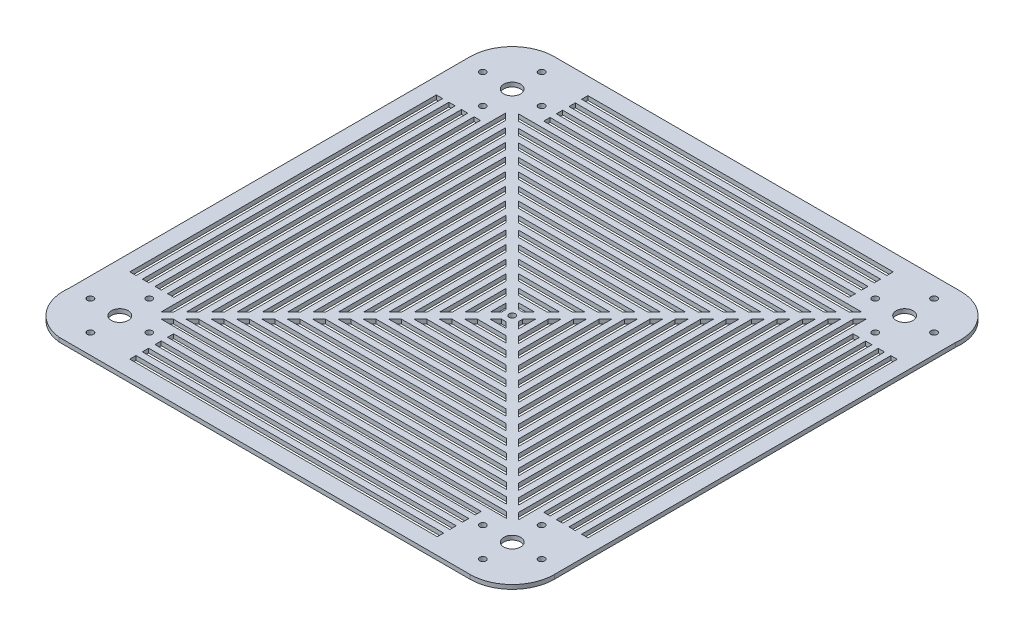
SolidWorks part; units mm, degrees
ref_plane "前视基准面" through (0, 0, 0) normal (0, 0, 1) x (1, 0, 0)
ref_plane "上视基准面" through (0, 0, 0) normal (0, 1, 0) x (1, 0, 0)
ref_plane "右视基准面" through (0, 0, 0) normal (1, 0, 0) x (0, 0, -1)
sketch "草图5" plane through (0, 0, 0) normal (0, 1, 0) x (1, 0, 0)
  line L0 (1.5, 6) -> (5.6645, 10.1645)
  line L5 (-145, 175.0001) -> (144.9999, 175.0001)
  line L6 (-175.0001, 145) -> (-175.0001, -141.539)
  line L7 (-148.4608, -175.0001) -> (145, -175.0001)
  line L8 (174.7909, 141.4627) -> (175.0001, -144.9781)
  line L9 (-175.0001, 175.0001) -> (175.0001, -175.0001) construction
  line L10 (-175, -175) -> (175, 175) construction
  line L13 (0, 0) -> (0, -50000) construction
  line L14 (0, 0) -> (50000, 0) construction
  line L15 (-1.5, 6) -> (1.5, 6)
  line L16 (-6, 1.5) -> (-6, -1.5)
  line L17 (-1.5, -6) -> (1.5, -6)
  line L18 (6, 1.5) -> (6, -1.5)
  line L19 (-6, 6) -> (6, -6) construction
  line L20 (-6, -6) -> (6, 6) construction
  line L21 (-5.6645, 10.1645) -> (5.6645, 10.1645)
  line L22 (-9.9532, 5.4462) -> (-9.9532, -5.4532)
  line L23 (-5.5915, -10.0915) -> (5.606, -10.0915)
  line L24 (10.5146, 6.0146) -> (10.5146, -6.0145)
  line L25 (-10.5, 10.5) -> (10.5, -10.5) construction
  line L26 (-10.5, -10.5) -> (10.5, 10.5) construction
  line L27 (-10.1536, 14.6536) -> (10.1536, 14.6536)
  line L28 (-14.4739, 9.959) -> (-14.4739, -9.9739)
  line L29 (-10.1115, -14.6115) -> (10.142, -14.6115)
  line L30 (15.0552, 10.5552) -> (15.0552, -10.5552)
  line L31 (-15, 15) -> (15, -15) construction
  line L32 (-15, -15) -> (15, 15) construction
  line L33 (-14.6429, 19.1429) -> (14.6428, 19.1429)
  line L34 (-18.9947, 14.4718) -> (-18.9947, -14.4947)
  line L35 (-14.6315, -19.1315) -> (14.678, -19.1315)
  line L36 (19.591, 15.091) -> (19.591, -15.0909)
  line L37 (-19.5, 19.5) -> (19.5, -19.5) construction
  line L38 (-19.5, -19.5) -> (19.5, 19.5) construction
  line L39 (-19.1322, 23.6322) -> (19.1321, 23.6322)
  line L40 (-23.5154, 18.9846) -> (-23.5154, -19.0154)
  line L41 (-19.1515, -23.6515) -> (19.214, -23.6515)
  line L42 (24.1268, 19.6268) -> (24.1268, -19.6267)
  line L43 (-24, 24) -> (24, -24) construction
  line L44 (-24, -24) -> (24, 24) construction
  line L45 (23.6214, 28.1215) -> (-23.6215, 28.1215)
  line L46 (28.6626, 24.1626) -> (28.6626, -24.1625)
  line L47 (23.75, -28.1715) -> (-23.6715, -28.1715)
  line L48 (-28.0362, 23.4973) -> (-28.0362, -23.5362)
  line L49 (28.5, 28.5) -> (-28.5, -28.5) construction
  line L50 (28.5, -28.5) -> (-28.5, 28.5) construction
  line L51 (-28.1108, 32.6108) -> (28.1106, 32.6108)
  line L52 (-32.5569, 28.0101) -> (-32.5569, -28.0569)
  line L53 (-28.1915, -32.6915) -> (28.286, -32.6915)
  line L54 (33.1984, 28.6984) -> (33.1984, -28.6983)
  line L55 (-33, 33) -> (33, -33) construction
  line L56 (-33, -33) -> (33, 33) construction
  line L57 (-32.6001, 37.1001) -> (32.5999, 37.1001)
  line L58 (-37.0777, 32.5229) -> (-37.0777, -32.5777)
  line L59 (-32.7115, -37.2115) -> (32.822, -37.2115)
  line L60 (37.7342, 33.2342) -> (37.7342, -33.2341)
  line L61 (-37.5, 37.5) -> (37.5, -37.5) construction
  line L62 (-37.5, -37.5) -> (37.5, 37.5) construction
  line L63 (-37.0894, 41.5894) -> (37.0891, 41.5894)
  line L64 (-41.5984, 37.0357) -> (-41.5984, -37.0984)
  line L65 (-37.2314, -41.7314) -> (37.358, -41.7314)
  line L66 (42.27, 37.77) -> (42.27, -37.7699)
  line L67 (-42, 42) -> (42, -42) construction
  line L68 (-42, -42) -> (42, 42) construction
  line L69 (-41.5787, 46.0787) -> (41.5784, 46.0787)
  line L70 (-46.1192, 41.5485) -> (-46.1192, -41.6192)
  line L71 (-41.7514, -46.2514) -> (41.894, -46.2514)
  line L72 (46.8058, 42.3058) -> (46.8058, -42.3057)
  line L73 (-46.5, 46.5) -> (46.5, -46.5) construction
  line L74 (-46.5, -46.5) -> (46.5, 46.5) construction
  line L75 (-46.068, 50.568) -> (46.0677, 50.568)
  line L76 (-50.6399, 46.0613) -> (-50.6399, -46.1399)
  line L77 (-46.2714, -50.7714) -> (46.43, -50.7714)
  line L78 (51.3416, 46.8416) -> (51.3416, -46.8415)
  line L79 (-51, 51) -> (51, -51) construction
  line L80 (-51, -51) -> (51, 51) construction
  line L81 (-50.5573, 55.0573) -> (50.5569, 55.0573)
  line L82 (-55.1607, 50.574) -> (-55.1607, -50.6607)
  line L83 (-50.7914, -55.2914) -> (50.9659, -55.2914)
  line L84 (55.8774, 51.3774) -> (55.8774, -51.3773)
  line L85 (-55.5, 55.5) -> (55.5, -55.5) construction
  line L86 (-55.5, -55.5) -> (55.5, 55.5) construction
  line L87 (-55.0466, 59.5466) -> (55.0462, 59.5466)
  line L88 (-59.6814, 55.0868) -> (-59.6814, -55.1814)
  line L89 (-55.3114, -59.8114) -> (55.5019, -59.8114)
  line L90 (60.4132, 55.9132) -> (60.4132, -55.913)
  line L91 (-60, 60) -> (60, -60) construction
  line L92 (-60, -60) -> (60, 60) construction
  line L93 (-59.5358, 64.0358) -> (59.5354, 64.0358)
  line L94 (-64.2022, 59.5996) -> (-64.2022, -59.7022)
  line L95 (-59.8314, -64.3314) -> (60.0379, -64.3314)
  line L96 (64.949, 60.449) -> (64.949, -60.4488)
  line L97 (-64.5, 64.5) -> (64.5, -64.5) construction
  line L98 (-64.5, -64.5) -> (64.5, 64.5) construction
  line L99 (-64.0251, 68.5251) -> (64.0247, 68.5251)
  line L100 (-68.7229, 64.1124) -> (-68.7229, -64.2229)
  line L101 (-64.3514, -68.8514) -> (64.5739, -68.8514)
  line L102 (69.4848, 64.9848) -> (69.4848, -64.9846)
  line L103 (-69, 69) -> (69, -69) construction
  line L104 (-69, -69) -> (69, 69) construction
  line L105 (-68.5144, 73.0144) -> (68.5139, 73.0144)
  line L106 (-73.2437, 68.6252) -> (-73.2437, -68.7437)
  line L107 (-68.8713, -73.3713) -> (69.1099, -73.3713)
  line L108 (74.0206, 69.5206) -> (74.0206, -69.5204)
  line L109 (-73.5, 73.5) -> (73.5, -73.5) construction
  line L110 (-73.5, -73.5) -> (73.5, 73.5) construction
  line L111 (-73.0037, 77.5037) -> (73.0032, 77.5037)
  line L112 (-77.7644, 73.138) -> (-77.7644, -73.2644)
  line L113 (-73.3913, -77.8913) -> (73.6459, -77.8913)
  line L114 (78.5564, 74.0564) -> (78.5564, -74.0562)
  line L115 (-78, 78) -> (78, -78) construction
  line L116 (-78, -78) -> (78, 78) construction
  line L117 (-77.493, 81.993) -> (77.4925, 81.993)
  line L118 (-82.2852, 77.6508) -> (-82.2852, -77.7852)
  line L119 (-77.9113, -82.4113) -> (78.1819, -82.4113)
  line L120 (83.0923, 78.5923) -> (83.0923, -78.592)
  line L121 (-82.5, 82.5) -> (82.5, -82.5) construction
  line L122 (-82.5, -82.5) -> (82.5, 82.5) construction
  line L123 (-81.9823, 86.4823) -> (81.9817, 86.4823)
  line L124 (-86.8059, 82.1635) -> (-86.8059, -82.3059)
  line L125 (-82.4313, -86.9313) -> (82.7179, -86.9313)
  line L126 (87.6281, 83.1281) -> (87.6281, -83.1278)
  line L127 (-87, 87) -> (87, -87) construction
  line L128 (-87, -87) -> (87, 87) construction
  line L129 (-86.4716, 90.9716) -> (86.471, 90.9716)
  line L130 (-91.3267, 86.6763) -> (-91.3267, -86.8267)
  line L131 (-86.9513, -91.4513) -> (87.2539, -91.4513)
  line L132 (92.1639, 87.6639) -> (92.1639, -87.6636)
  line L133 (-91.5, 91.5) -> (91.5, -91.5) construction
  line L134 (-91.5, -91.5) -> (91.5, 91.5) construction
  line L135 (-90.9609, 95.4609) -> (90.9602, 95.4609)
  line L136 (-95.8474, 91.1891) -> (-95.8474, -91.3474)
  line L137 (-91.4713, -95.9713) -> (91.7899, -95.9713)
  line L138 (96.6997, 92.1997) -> (96.6997, -92.1994)
  line L139 (-96, 96) -> (96, -96) construction
  line L140 (-96, -96) -> (96, 96) construction
  line L141 (-95.4502, 99.9502) -> (95.4495, 99.9502)
  line L142 (-100.3682, 95.7019) -> (-100.3682, -95.8682)
  line L143 (-95.9913, -100.4913) -> (96.3259, -100.4913)
  line L144 (101.2355, 96.7355) -> (101.2355, -96.7351)
  line L145 (-100.5, 100.5) -> (100.5, -100.5) construction
  line L146 (-100.5, -100.5) -> (100.5, 100.5) construction
  line L147 (-99.9395, 104.4395) -> (99.9388, 104.4395)
  line L148 (-104.8889, 100.2147) -> (-104.8889, -100.3889)
  line L149 (-100.5113, -105.0113) -> (100.8619, -105.0113)
  line L150 (105.7713, 101.2713) -> (105.7713, -101.2709)
  line L151 (-105, 105) -> (105, -105) construction
  line L152 (-105, -105) -> (105, 105) construction
  line L153 (-104.4288, 108.9288) -> (104.428, 108.9288)
  line L154 (-109.4097, 104.7275) -> (-109.4097, -104.9097)
  line L155 (-105.0312, -109.5312) -> (105.3979, -109.5312)
  line L156 (110.3071, 105.8071) -> (110.3071, -105.8067)
  line L157 (-109.5, 109.5) -> (109.5, -109.5) construction
  line L158 (-109.5, -109.5) -> (109.5, 109.5) construction
  line L159 (-108.918, 113.418) -> (108.9173, 113.418)
  line L160 (-113.9304, 109.2402) -> (-113.9304, -109.4304)
  line L161 (-109.5512, -114.0512) -> (109.9339, -114.0512)
  line L162 (114.8429, 110.3429) -> (114.8429, -110.3425)
  line L163 (-114, 114) -> (114, -114) construction
  line L164 (-114, -114) -> (114, 114) construction
  line L165 (-113.4073, 117.9073) -> (113.4065, 117.9073)
  line L166 (-118.4512, 113.753) -> (-118.4512, -113.9512)
  line L167 (-114.0712, -118.5712) -> (114.4699, -118.5712)
  line L168 (119.3787, 114.8787) -> (119.3787, -114.8783)
  line L169 (-118.5, 118.5) -> (118.5, -118.5) construction
  line L170 (-118.5, -118.5) -> (118.5, 118.5) construction
  line L171 (-117.8966, 122.3966) -> (117.8958, 122.3966)
  line L172 (-122.9719, 118.2658) -> (-122.9719, -118.4719)
  line L173 (-118.5912, -123.0912) -> (119.0058, -123.0912)
  line L174 (123.9145, 119.4145) -> (123.9145, -119.4141)
  line L175 (-123, 123) -> (123, -123) construction
  line L176 (-123, -123) -> (123, 123) construction
  line L177 (-122.3859, 126.8859) -> (122.385, 126.8859)
  line L178 (-127.503, 122.7889) -> (-127.503, -123.003)
  line L179 (-122.9106, -127.4106) -> (123.3406, -127.4106)
  line L180 (128.4503, 123.9503) -> (128.4503, -123.9499)
  line L181 (-127.5, 127.5) -> (127.5, -127.5) construction
  line L182 (-127.5, -127.5) -> (127.5, 127.5) construction
  line L183 (-108.918, 131.418) -> (108.9173, 131.418)
  line L184 (-131.9304, 109.2402) -> (-131.9304, -109.4304)
  line L185 (-109.5512, -132.0657) -> (109.9339, -132.0657)
  line L186 (132.8429, 110.3429) -> (132.8429, -110.3425)
  line L187 (-132, 132) -> (132, -132) construction
  line L188 (-132, -132) -> (132, 132) construction
  line L189 (6, 1.5) -> (10.5146, 6.0146)
  line L190 (6, -1.5) -> (10.5146, -6.0145)
  line L191 (1.5, -6) -> (5.606, -10.0915)
  line L192 (-1.5, -6) -> (-5.5915, -10.0915)
  line L193 (-6, -1.5) -> (-9.9532, -5.4532)
  line L194 (-1.5, 6) -> (-5.6645, 10.1645)
  line L195 (-6, 1.5) -> (-9.9532, 5.4462)
  line L196 (10.1536, 14.6536) -> (14.6428, 19.1429)
  line L197 (15.0552, 10.5552) -> (19.591, 15.091)
  line L198 (24.1268, 19.6268) -> (28.6626, 24.1626)
  line L199 (19.1321, 23.6322) -> (23.6214, 28.1215)
  line L200 (28.1106, 32.6108) -> (32.5999, 37.1001)
  line L201 (33.1984, 28.6984) -> (37.7342, 33.2342)
  line L202 (42.27, 37.77) -> (46.8058, 42.3058)
  line L203 (37.0891, 41.5894) -> (41.5784, 46.0787)
  line L204 (46.0677, 50.568) -> (50.5569, 55.0573)
  line L205 (51.3416, 46.8416) -> (55.8774, 51.3774)
  line L206 (55.0462, 59.5466) -> (59.5354, 64.0358)
  line L207 (60.4132, 55.9132) -> (64.949, 60.449)
  line L208 (64.0247, 68.5251) -> (68.5139, 73.0144)
  line L209 (69.4848, 64.9848) -> (74.0206, 69.5206)
  line L210 (73.0032, 77.5037) -> (77.4925, 81.993)
  line L211 (78.5564, 74.0564) -> (83.0923, 78.5923)
  line L212 (81.9817, 86.4823) -> (86.471, 90.9716)
  line L213 (87.6281, 83.1281) -> (92.1639, 87.6639)
  line L214 (90.9602, 95.4609) -> (95.4495, 99.9502)
  line L215 (96.6997, 92.1997) -> (101.2355, 96.7355)
  line L216 (99.9388, 104.4395) -> (104.428, 108.9288)
  line L217 (105.7713, 101.2713) -> (110.3071, 105.8071)
  line L218 (108.9173, 113.418) -> (113.4065, 117.9073)
  line L219 (114.8429, 110.3429) -> (119.3787, 114.8787)
  line L220 (117.8958, 122.3966) -> (122.385, 126.8859)
  line L221 (123.9145, 119.4145) -> (128.4503, 123.9503)
  line L222 (146.3429, 110.3429) -> (146.3429, -110.3425)
  line L223 (109.9339, -132.0657) -> (109.9339, -136.3666)
  line L224 (-14.4739, 9.959) -> (-18.9947, 14.4718)
  line L225 (-10.1536, 14.6536) -> (-14.6429, 19.1429)
  line L226 (-14.4739, -9.9739) -> (-18.9947, -14.4947)
  line L227 (-10.1115, -14.6115) -> (-14.6315, -19.1315)
  line L228 (15.0552, -10.5552) -> (19.591, -15.0909)
  line L229 (10.142, -14.6115) -> (14.678, -19.1315)
  line L230 (-23.5154, 18.9846) -> (-28.0362, 23.4973)
  line L231 (-19.1322, 23.6322) -> (-23.6215, 28.1215)
  line L232 (-32.5569, 28.0101) -> (-37.0777, 32.5229)
  line L233 (-28.1108, 32.6108) -> (-32.6001, 37.1001)
  line L234 (-37.0894, 41.5894) -> (-41.5787, 46.0787)
  line L235 (-41.5984, 37.0357) -> (-46.1192, 41.5485)
  line L236 (-50.6399, 46.0613) -> (-55.1607, 50.574)
  line L237 (-46.068, 50.568) -> (-50.5573, 55.0573)
  line L238 (-59.6814, 55.0868) -> (-64.2022, 59.5996)
  line L239 (-55.0466, 59.5466) -> (-59.5358, 64.0358)
  line L240 (-68.7229, 64.1124) -> (-73.2437, 68.6252)
  line L241 (-64.0251, 68.5251) -> (-68.5144, 73.0144)
  line L242 (-73.0037, 77.5037) -> (-77.493, 81.993)
  line L243 (-77.7644, 73.138) -> (-82.2852, 77.6508)
  line L244 (-81.9823, 86.4823) -> (-86.4716, 90.9716)
  line L245 (-86.8059, 82.1635) -> (-91.3267, 86.6763)
  line L246 (-95.8474, 91.1891) -> (-100.3682, 95.7019)
  line L247 (-90.9609, 95.4609) -> (-95.4502, 99.9502)
  line L248 (-104.8889, 100.2147) -> (-109.4097, 104.7275)
  line L249 (-99.9395, 104.4395) -> (-104.4288, 108.9288)
  line L250 (-113.9304, 109.2402) -> (-118.4512, 113.753)
  line L251 (-108.918, 113.418) -> (-113.4073, 117.9073)
  line L252 (-122.9719, 118.2658) -> (-127.503, 122.7889)
  line L253 (-117.8966, 122.3966) -> (-122.3859, 126.8859)
  line L254 (-108.918, 135.918) -> (108.9173, 135.918)
  line L255 (-158.9304, 109.2402) -> (-163.4304, 109.2402)
  line L256 (-19.1515, -23.6515) -> (-23.6715, -28.1715)
  line L257 (-23.5154, -19.0154) -> (-28.0362, -23.5362)
  line L258 (24.1268, -19.6267) -> (28.6626, -24.1625)
  line L259 (19.214, -23.6515) -> (23.75, -28.1715)
  line L260 (-32.5569, -28.0569) -> (-37.0777, -32.5777)
  line L261 (-28.1915, -32.6915) -> (-32.7115, -37.2115)
  line L262 (-41.5984, -37.0984) -> (-46.1192, -41.6192)
  line L263 (-37.2314, -41.7314) -> (-41.7514, -46.2514)
  line L264 (-50.6399, -46.1399) -> (-55.1607, -50.6607)
  line L265 (-46.2714, -50.7714) -> (-50.7914, -55.2914)
  line L266 (-59.6814, -55.1814) -> (-64.2022, -59.7022)
  line L267 (-55.3114, -59.8114) -> (-59.8314, -64.3314)
  line L268 (-68.7229, -64.2229) -> (-73.2437, -68.7437)
  line L269 (-64.3514, -68.8514) -> (-68.8713, -73.3713)
  line L270 (-77.7644, -73.2644) -> (-82.2852, -77.7852)
  line L271 (-73.3913, -77.8913) -> (-77.9113, -82.4113)
  line L272 (-86.8059, -82.3059) -> (-91.3267, -86.8267)
  line L273 (-82.4313, -86.9313) -> (-86.9513, -91.4513)
  line L274 (-95.8474, -91.3474) -> (-100.3682, -95.8682)
  line L275 (-91.4713, -95.9713) -> (-95.9913, -100.4913)
  line L276 (-104.8889, -100.3889) -> (-109.4097, -104.9097)
  line L277 (-100.5113, -105.0113) -> (-105.0312, -109.5312)
  line L278 (-113.9304, -109.4304) -> (-118.4512, -113.9512)
  line L279 (-109.5512, -114.0512) -> (-114.0712, -118.5712)
  line L280 (-122.9719, -118.4719) -> (-127.503, -123.003)
  line L281 (-118.5912, -123.0912) -> (-122.9106, -127.4106)
  line L282 (-109.5512, -136.3666) -> (109.9339, -136.3666)
  line L283 (-109.5512, -136.3666) -> (-109.5512, -132.0657)
  line L284 (33.1984, -28.6983) -> (37.7342, -33.2341)
  line L285 (28.286, -32.6915) -> (32.822, -37.2115)
  line L286 (42.27, -37.7699) -> (46.8058, -42.3057)
  line L287 (37.358, -41.7314) -> (41.894, -46.2514)
  line L288 (51.3416, -46.8415) -> (55.8774, -51.3773)
  line L289 (46.43, -50.7714) -> (50.9659, -55.2914)
  line L290 (60.4132, -55.913) -> (64.949, -60.4488)
  line L291 (55.5019, -59.8114) -> (60.0379, -64.3314)
  line L292 (69.4848, -64.9846) -> (74.0206, -69.5204)
  line L293 (64.5739, -68.8514) -> (69.1099, -73.3713)
  line L294 (78.5564, -74.0562) -> (83.0923, -78.592)
  line L295 (73.6459, -77.8913) -> (78.1819, -82.4113)
  line L296 (87.6281, -83.1278) -> (92.1639, -87.6636)
  line L297 (82.7179, -86.9313) -> (87.2539, -91.4513)
  line L298 (91.7899, -95.9713) -> (96.3259, -100.4913)
  line L299 (96.6997, -92.1994) -> (101.2355, -96.7351)
  line L300 (105.7713, -101.2709) -> (110.3071, -105.8067)
  line L301 (100.8619, -105.0113) -> (105.3979, -109.5312)
  line L302 (109.9339, -114.0512) -> (114.4699, -118.5712)
  line L303 (114.8429, -110.3425) -> (119.3787, -114.8783)
  line L304 (123.9145, -119.4141) -> (128.4503, -123.9499)
  line L305 (119.0058, -123.0912) -> (123.3406, -127.4106)
  line L308 (-131.9304, -109.4304) -> (-136.4304, -109.4304)
  line L312 (137.3429, 110.3429) -> (137.3429, -110.3425)
  line L313 (-136.5, 136.5) -> (136.5, -136.5) construction
  line L314 (-136.5, -136.5) -> (136.5, 136.5) construction
  line L317 (-109.5512, -140.8666) -> (109.9339, -140.8666)
  line L319 (-141, 141) -> (141, -141) construction
  line L320 (-141, -141) -> (141, 141) construction
  line L325 (-145.5, 145.5) -> (145.5, -145.5) construction
  line L326 (-145.5, -145.5) -> (145.5, 145.5) construction
  line L327 (-108.918, 149.418) -> (108.9173, 149.418)
  line L328 (-149.9304, 109.2402) -> (-149.9304, -109.4304)
  line L329 (-109.5512, -149.8666) -> (109.9339, -149.8666)
  line L330 (150.8429, 110.3429) -> (150.8429, -110.3425)
  line L331 (-150, 150) -> (150, -150) construction
  line L332 (-150, -150) -> (150, 150) construction
  line L333 (-108.918, 153.918) -> (108.9173, 153.918)
  line L334 (-154.4304, 109.2402) -> (-154.4304, -109.4304)
  line L335 (-109.5512, -154.3666) -> (109.9339, -154.3666)
  line L336 (155.3429, 110.3429) -> (155.3429, -110.3425)
  line L337 (-154.5, 154.5) -> (154.5, -154.5) construction
  line L338 (-154.5, -154.5) -> (154.5, 154.5) construction
  line L343 (-159, 159) -> (159, -159) construction
  line L344 (-159, -159) -> (159, 159) construction
  line L345 (-108.918, 162.918) -> (108.9173, 162.918)
  line L346 (-163.4304, 109.2402) -> (-163.4304, -109.4304)
  line L347 (-109.5512, -163.3666) -> (109.9339, -163.3666)
  line L348 (164.3429, 110.3429) -> (164.3429, -110.3425)
  line L349 (-163.5, 163.5) -> (163.5, -163.5) construction
  line L350 (-163.5, -163.5) -> (163.5, 163.5) construction
  line L351 (-109.5512, -163.3666) -> (-109.5512, -158.8666)
  line L352 (-109.5512, -145.3666) -> (-109.5512, -140.8666)
  line L353 (-109.5512, -154.3666) -> (-109.5512, -149.8666)
  line L354 (-109.5512, -158.8666) -> (109.9339, -158.8666)
  line L355 (-140.9304, -109.4304) -> (-145.4304, -109.4304)
  line L356 (-109.5512, -145.3666) -> (109.9339, -145.3666)
  line L357 (-149.9304, -109.4304) -> (-154.4304, -109.4304)
  line L358 (-158.9304, -109.4304) -> (-163.4304, -109.4304)
  line L359 (-131.9304, 109.2402) -> (-136.4304, 109.2402)
  line L360 (-108.918, 131.418) -> (-108.918, 135.918)
  line L361 (-158.9304, 109.2402) -> (-158.9304, -109.4304)
  line L362 (-145.4304, 109.2402) -> (-145.4304, -109.4304)
  line L363 (-140.9304, 109.2402) -> (-140.9304, -109.4304)
  line L364 (-136.4304, 109.2402) -> (-136.4304, -109.4304)
  line L365 (-108.918, 140.418) -> (108.9173, 140.418)
  line L366 (-108.918, 144.918) -> (108.9173, 144.918)
  line L367 (-149.9304, 109.2402) -> (-154.4304, 109.2402)
  line L368 (-140.9304, 109.2402) -> (-145.4304, 109.2402)
  line L369 (-108.918, 158.418) -> (108.9173, 158.418)
  line L370 (-108.918, 158.418) -> (-108.918, 162.918)
  line L371 (-108.918, 149.418) -> (-108.918, 153.918)
  line L372 (-108.918, 140.418) -> (-108.918, 144.918)
  line L373 (108.9173, 131.418) -> (108.9173, 135.918)
  line L374 (132.8429, 110.3429) -> (137.3429, 110.3429)
  line L375 (108.9173, 158.418) -> (108.9173, 162.918)
  line L376 (108.9173, 149.418) -> (108.9173, 153.918)
  line L377 (141.8429, 110.3429) -> (146.3429, 110.3429)
  line L378 (150.8429, 110.3429) -> (155.3429, 110.3429)
  line L379 (159.8429, 110.3429) -> (164.3429, 110.3429)
  line L380 (108.9173, 140.418) -> (108.9173, 144.918)
  line L381 (141.8429, 110.3429) -> (141.8429, -110.3425)
  line L382 (159.8429, 110.3429) -> (159.8429, -110.3425)
  line L383 (132.8429, -110.3425) -> (137.3429, -110.3425)
  line L384 (109.9339, -158.8666) -> (109.9339, -163.3666)
  line L385 (109.9339, -149.8666) -> (109.9339, -154.3666)
  line L386 (109.9339, -140.8666) -> (109.9339, -145.3666)
  line L387 (141.8429, -110.3425) -> (146.3429, -110.3425)
  line L388 (150.8429, -110.3425) -> (155.3429, -110.3425)
  line L389 (159.8429, -110.3425) -> (164.3429, -110.3425)
  arc A0 (174.7909, 141.4627) -> (144.9999, 175.0001) centre (144.9999, 144.9999) ccw
  arc A1 (175.0001, -144.9781) -> (145, -175.0001) centre (145, -145) cw
  arc A2 (-148.4608, -175.0001) -> (-175.0001, -141.539) centre (-144.9999, -144.9999) cw
  arc A3 (-175.0001, 145) -> (-145, 175.0001) centre (-145, 145) cw
  circle A5 centre (140, 119) radius 2.25
  circle A6 centre (161, 140) radius 2.25
  circle A7 centre (140, 161) radius 2.25
  circle A8 centre (119, 140) radius 2.25
  circle A9 centre (140, 140) radius 6.02
  circle A11 centre (140, -161) radius 2.25
  circle A12 centre (161, -140) radius 2.25
  circle A13 centre (140, -119) radius 2.25
  circle A14 centre (119, -140) radius 2.25
  circle A15 centre (140, -140) radius 6.02
  circle A17 centre (-140, 119) radius 2.25
  circle A18 centre (-119, 140) radius 2.25
  circle A19 centre (-140, 161) radius 2.25
  circle A20 centre (-161, 140) radius 2.25
  circle A21 centre (-140, 140) radius 6.02
  circle A23 centre (-140, -161) radius 2.25
  circle A24 centre (-119, -140) radius 2.25
  circle A25 centre (-140, -119) radius 2.25
  circle A26 centre (-161, -140) radius 2.25
  circle A27 centre (-140, -140) radius 6.02
  circle A28 centre (0, 0) radius 2.25
  point P0 (0, 0)
  point P5 (144.9999, 144.9999)
  point P19 (140, 140)
  point P31 (140, -140)
  point P32 (-140, 140)
  point P57 (-140, -140)
extrude "凸台-拉伸1" add sketch "草图5" along normal blind 3
